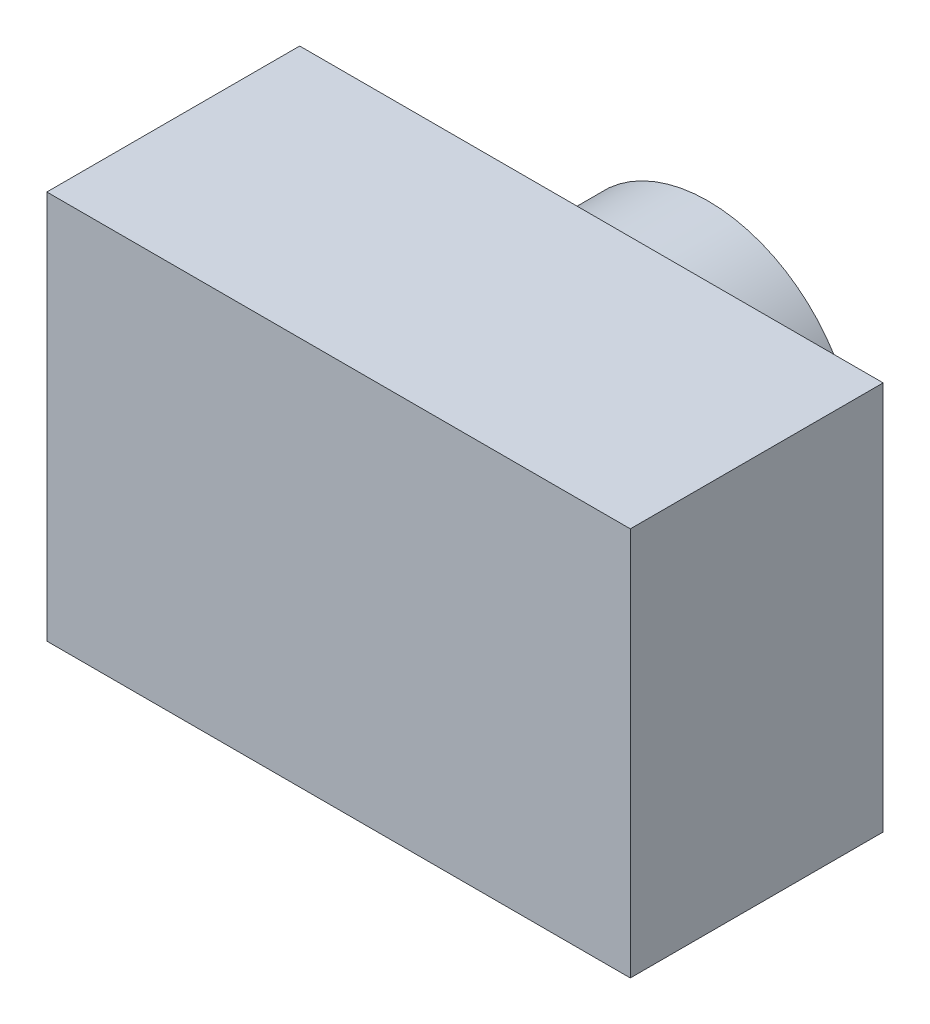
SolidWorks part; units mm, degrees
ref_plane "Front" through (0, 0, 0) normal (0, 0, 1) x (1, 0, 0)
ref_plane "Top" through (0, 0, 0) normal (0, 1, 0) x (1, 0, 0)
ref_plane "Right" through (0, 0, 0) normal (1, 0, 0) x (0, 0, -1)
sketch "草图1" plane through (0, 0, 0) normal (0, 0, 1) x (1, 0, 0)
  line L1 (-75, 50) -> (75, 50)
  line L2 (-75, 50) -> (-75, -50)
  line L3 (-75, -50) -> (75, -50)
  line L4 (75, 50) -> (75, -50)
  line L5 (-75, 50) -> (75, -50) construction
  line L6 (-75, -50) -> (75, 50) construction
  point P0 (0, 0)
extrude "凸台-拉伸1" add sketch "草图1" along normal blind 65
ref_plane "基准面1" through (0, 0, 60) normal (0, 0, 1) x (1, 0, 0)
sketch "草图4" plane through (0, 0, 60) normal (0, 0, 1) x (1, 0, 0)
  line L8 (70, -45) -> (70, 45)
  line L9 (70, 45) -> (-70, 45)
  line L10 (-70, 45) -> (-70, -45)
  line L11 (-70, -45) -> (70, -45)
  line L12 (70, -45) -> (70, 45)
  line L13 (70, 45) -> (-70, 45)
  line L14 (-70, 45) -> (-70, -45)
  line L15 (-70, -45) -> (70, -45)
  dimension "D1" = 5
extrude "切除-拉伸1" cut sketch "草图4" against normal blind 55
sketch "草图5" plane through (0, 0, 0) normal (0, 0, -1) x (-1, 0, 0)
  circle A0 centre (0, 0) radius 38
  dimension "D1" = 76
extrude "凸台-拉伸2" add sketch "草图5" along normal blind 30
ref_plane "基准面2" through (0, 0, 0) normal (0, 0, 1) x (1, 0, 0)
sketch "草图7" plane through (0, 0, 0) normal (0, 0, 1) x (1, 0, 0)
  line L0 (-27.2834, 54.7645) -> (-27.2834, -54.9622)
